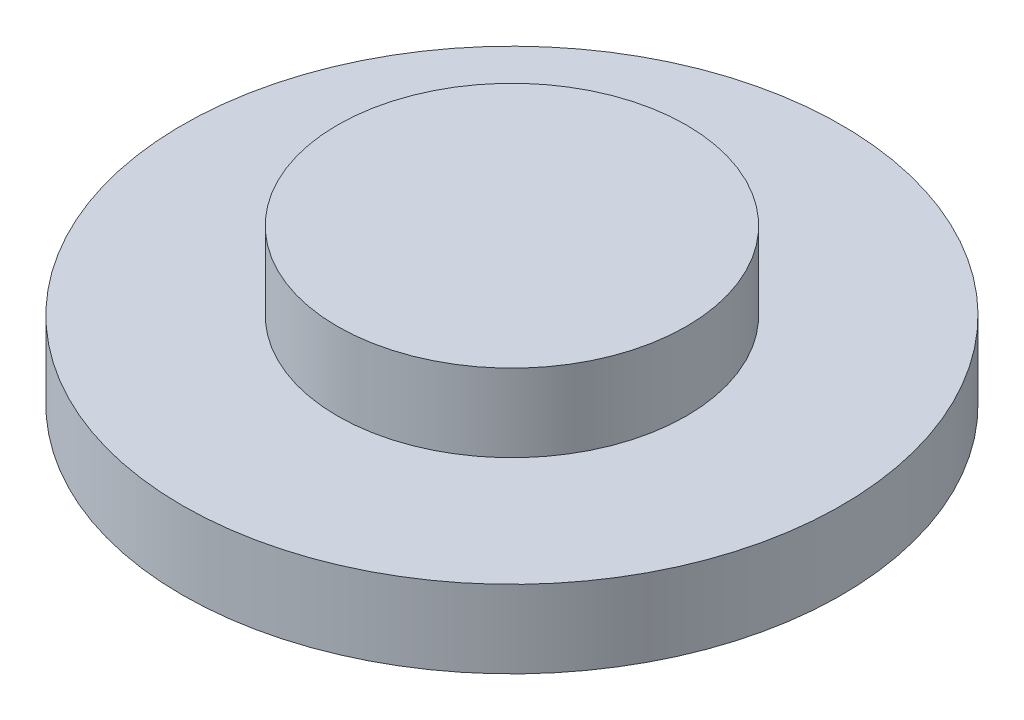
SolidWorks part; units mm, degrees
ref_plane "Front Plane" through (0, 0, 0) normal (0, 0, 1) x (1, 0, 0)
ref_plane "Top Plane" through (0, 0, 0) normal (0, 1, 0) x (1, 0, 0)
ref_plane "Right Plane" through (0, 0, 0) normal (1, 0, 0) x (0, 0, -1)
sketch "Sketch1" plane through (0, 0, 0) normal (0, 1, 0) x (1, 0, 0)
  circle A0 centre (0, 0) radius 8.5
  dimension "D1" = 17
extrude "Boss-Extrude2" add sketch "Sketch1" along normal blind 2
sketch "Sketch2" plane through (0, 2, 0) normal (0, 1, 0) x (1, 0, 0)
  circle A0 centre (0, 0) radius 4.5
  dimension "D1" = 9
extrude "Boss-Extrude3" add sketch "Sketch2" along normal blind 2
sketch "Sketch3" plane through (0, 0, 0) normal (0, -1, 0) x (1, 0, 0)
sketch "Sketch4" plane through (0, 0, 0) normal (0, -1, 0) x (1, 0, 0)
  circle A0 centre (0, 0) radius 4.75
  dimension "D1" = 9.5
extrude "Cut-Extrude1" cut sketch "Sketch4" against normal blind 1
